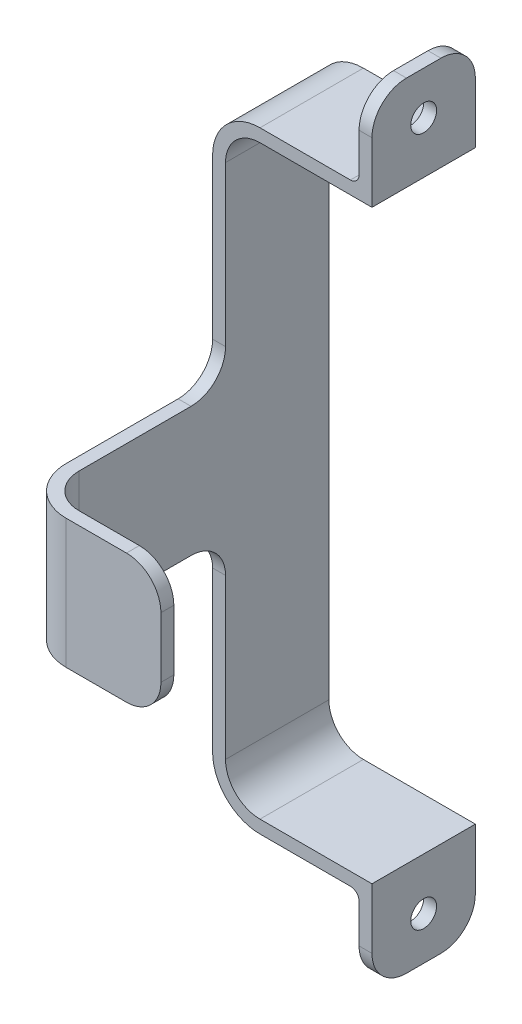
SolidWorks part; units mm, degrees
material "ABS"
ref_plane "Plan de face" through (0, 0, 0) normal (0, 0, 1) x (1, 0, 0)
ref_plane "Plan de dessus" through (0, 0, 0) normal (0, 1, 0) x (1, 0, 0)
ref_plane "Plan de droite" through (0, 0, 0) normal (1, 0, 0) x (0, 0, -1)
sketch "Esquisse1" plane through (0, 0, 0) normal (0, 0, 1) x (1, 0, 0)
  line L0 (0, 34) -> (0, 45)
  line L1 (0, 34) -> (-13, 34)
  line L2 (0, 34) -> (0, -34) construction
  line L3 (0, -34) -> (-13, -34)
  line L4 (-17, 30) -> (-17, -30)
  line L5 (0, -34) -> (0, -45)
  arc A0 (-13, -34) -> (-17, -30) centre (-13, -30) cw
  arc A1 (-13, 34) -> (-17, 30) centre (-13, 30) ccw
  dimension "D1" = 4
  dimension "D2" = 68
  dimension "D3" = 17
  dimension "D4" = 11
  dimension "D5" = 90
extrude "Extru.-Mince1" add sketch "Esquisse1" along normal mid plane 12 thin thin type one direction wall 1.5
sketch "Esquisse2" plane through (0, 0, 0) normal (0, 1, 0) x (1, 0, 0)
  line L0 (-17, -6) -> (-17, -23)
  line L1 (-13, -27) -> (-2, -27)
  arc A0 (-17, -23) -> (-13, -27) centre (-13, -23) ccw
  dimension "D1" = 15
  dimension "D2" = 4
  dimension "D3" = 21
extrude "Extru.-Mince2" add sketch "Esquisse2" along normal mid plane 15 thin
fillet "Congé1" radius 4 8 edges at (-0.75, 45, -6) (-0.75, 45, 6) (-2, 7.5, 27.75) (-2, -7.5, 27.75) (-0.75, -45, -6) (-0.75, -45, 6)
fillet "Congé2" radius 1 2 edges at (-1.5, 35.5, 0) (-1.5, -35.5, 0)
sketch "Esquisse3" plane through (0, 0, 0) normal (1, 0, 0) x (0, 0, -1)
  line L0 (6, 0) -> (0, 0) construction
  line L1 (6, 30) -> (6, -30) construction
  line L2 (-2, 45) -> (2, 45) construction
  circle A0 centre (0, 40) radius 1.5
  circle A1 centre (0, -40) radius 1.5
  dimension "D1" = 3
  dimension "D2" = 5
extrude "Enlèv. mat.-Extru.1" cut sketch "Esquisse3" against normal through all
